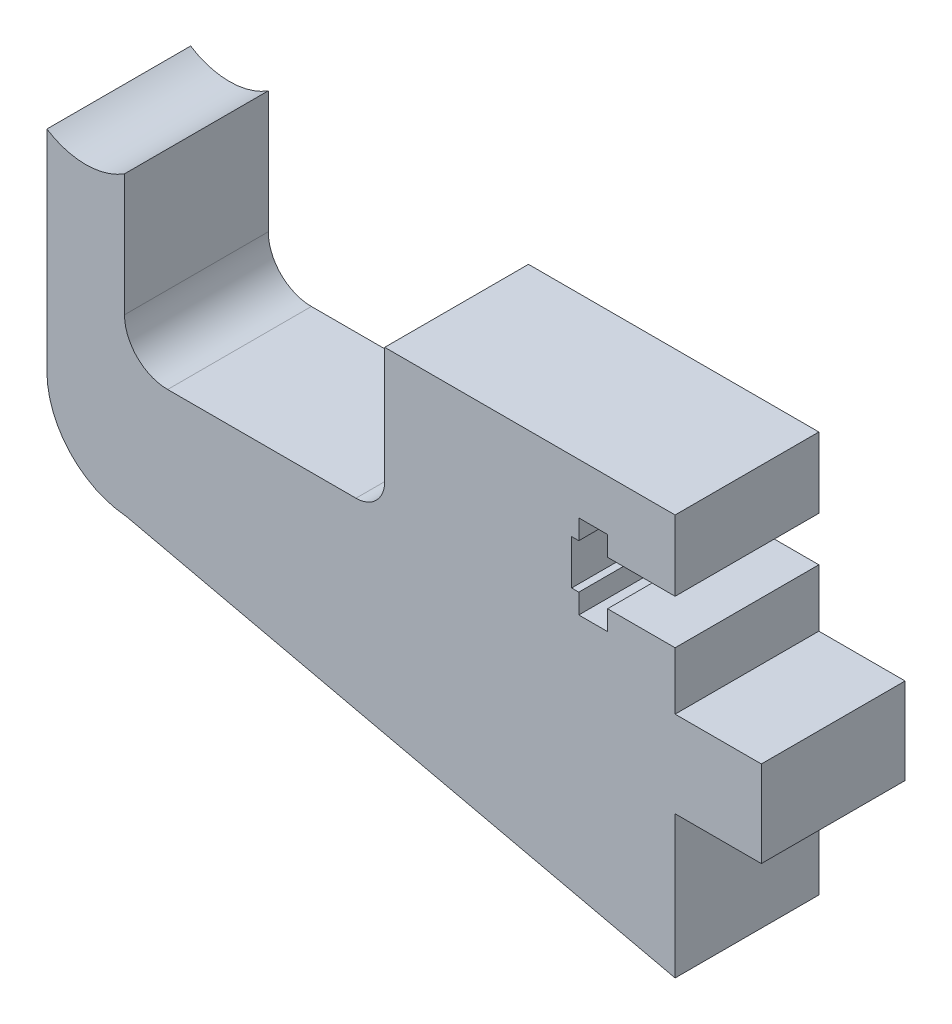
SolidWorks part; units mm, degrees
ref_plane "Płaszczyzna przednia" through (0, 0, 0) normal (0, 0, 1) x (1, 0, 0)
ref_plane "Płaszczyzna górna" through (0, 0, 0) normal (0, 1, 0) x (1, 0, 0)
ref_plane "Płaszczyzna prawa" through (0, 0, 0) normal (1, 0, 0) x (0, 0, -1)
sketch "Szkic1" plane through (0, 0, 0) normal (0, 0, 1) x (1, 0, 0)
  line L0 (-327.8528, -473.3082) -> (-327.8528, -478.4088)
  line L1 (-320.1028, -482.4088) -> (-311.7528, -482.4088)
  line L3 (-327.8528, -478.4088) -> (-327.8528, -479.4088)
  line L4 (-294.2528, -477.2189) -> (-289.5528, -477.2189)
  line L5 (-300.5528, -472.3189) -> (-289.5528, -472.3189)
  line L6 (-294.2528, -480.3189) -> (-289.5528, -480.3189)
  line L8 (-333.2528, -470.9172) -> (-333.2528, -485.5149)
  line L9 (-300.5528, -472.3189) -> (-309.7528, -472.3189)
  line L10 (-327.8528, -473.3082) -> (-327.8528, -470.9172)
  line L11 (-320.1028, -482.4088) -> (-324.8528, -482.4088)
  line L13 (-296.7528, -477.2189) -> (-296.7528, -480.3189)
  line L14 (-296.2528, -475.8439) -> (-296.2528, -477.2189)
  line L15 (-296.2528, -475.8439) -> (-294.2528, -475.8439)
  line L16 (-296.2528, -481.6939) -> (-294.2528, -481.6939)
  line L17 (-294.2528, -475.8439) -> (-294.2528, -477.2189)
  line L18 (-296.2528, -480.3189) -> (-296.2528, -481.6939)
  line L19 (-296.2528, -480.3189) -> (-296.7528, -480.3189)
  line L20 (-296.2528, -477.2189) -> (-296.7528, -477.2189)
  line L21 (-294.2528, -480.3189) -> (-294.2528, -481.6939)
  line L22 (-289.5528, -480.3189) -> (-289.5528, -484.3189)
  line L24 (-289.5528, -477.2189) -> (-289.5528, -472.3189)
  line L25 (-289.5528, -526.4001) -> (-289.5528, -468.9501) construction
  line L26 (-283.5528, -490.3189) -> (-289.5528, -490.3189)
  line L30 (-283.5528, -526.4001) -> (-283.5528, -468.9501) construction
  line L31 (-289.5528, -484.3189) -> (-283.5528, -484.3189)
  line L32 (-289.5528, -494.3159) -> (-289.5528, -500.2133)
  line L34 (-289.5528, -490.3189) -> (-289.5528, -494.3159)
  line L35 (-283.5528, -484.3189) -> (-283.5528, -490.3189)
  line L36 (-289.5528, -500.2133) -> (-327.7234, -491.4964)
  line L38 (-309.7528, -472.3189) -> (-309.7528, -480.4088)
  arc A0 (-327.8528, -470.9172) -> (-333.2528, -470.9172) centre (-330.5528, -466.7088) cw
  arc A1 (-311.7528, -482.4088) -> (-309.7528, -480.4088) centre (-311.7528, -480.4088) ccw
  arc A2 (-327.7234, -491.4964) -> (-333.2528, -485.5149) centre (-327.2528, -485.5149) cw
  circle A3 centre (-330.5528, -466.7088) radius 5 construction
  arc A5 (-324.8528, -482.4088) -> (-327.8528, -479.4088) centre (-324.8528, -479.4088) cw
  dimension "D3" = 5
  dimension "D13" = 4.7
  dimension "D2" = 6
  dimension "D5" = 3
  dimension "D6" = 2
  dimension "D4" = 2.7
  dimension "D9" = 5.85
  dimension "D10" = 1.375
  dimension "D11" = 2
  dimension "D12" = 0.5
extrude "Dodanie-wyciągnięcie1" add sketch "Szkic1" along normal blind 10
equation "\"tolerancja_wpusy\"=0.2"
equation "\"dlugosc_wpustu_duzy\"=20"
equation "\"srednica_otworu_M3\"=3.1"
equation "\"szerokosc_nogi_T\"=3.1"
equation "\"dlugosc_T_30\"=11"
equation "\"grubosc_na_nakretke_kwadrat\"=2"
equation "\"szerokosc_na_nakretke_kwadrat\"=5.85"
equation "\"wyokosc_nadstawki_T\"=0.5"
equation "\"D9@Szkic1\" = \"szerokosc_na_nakretke_kwadrat\""
equation "\"D10@Szkic1\"=(\"szerokosc_na_nakretke_kwadrat\"-\"szerokosc_nogi_T\")/2"
equation "\"D11@Szkic1\"=\"grubosc_na_nakretke_kwadrat\""
equation "\"D12@Szkic1\"=\"wyokosc_nadstawki_T\""
